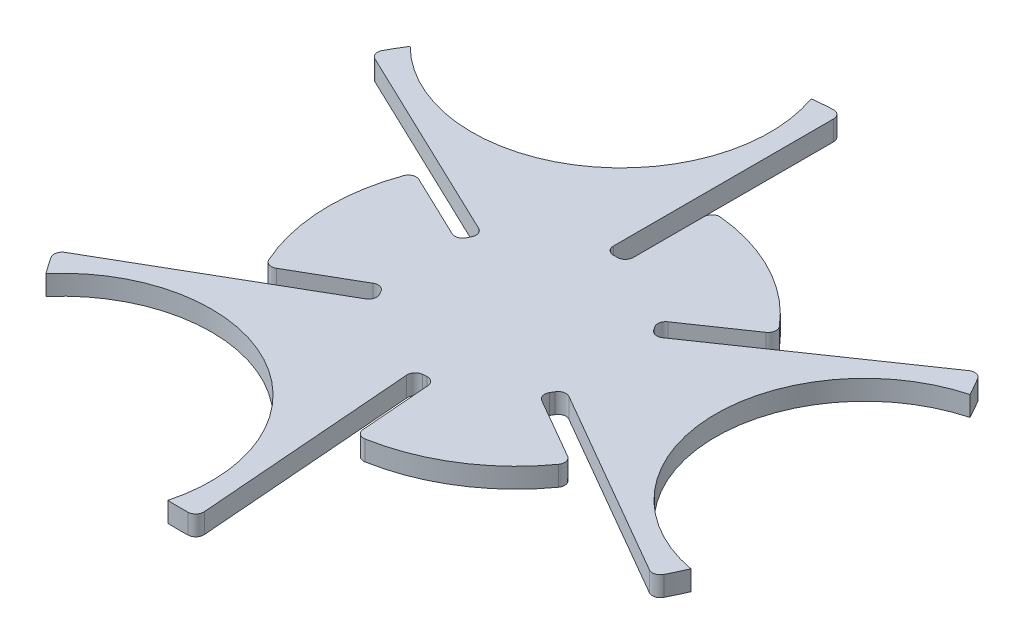
SolidWorks part; units mm, degrees
ref_plane "前基準面" through (0, 0, 0) normal (0, 0, 1) x (1, 0, 0)
ref_plane "上基準面" through (0, 0, 0) normal (0, 1, 0) x (1, 0, 0)
ref_plane "右基準面" through (0, 0, 0) normal (1, 0, 0) x (0, 0, -1)
sketch "草圖1" plane through (0, 0, 0) normal (0, 1, 0) x (1, 0, 0)
  line L2 (41.8956, -21.3017) -> (22.9006, -10.3349)
  line L8 (-2.5, 46.9335) -> (-2.5, 25)
  line L9 (-2.5, 25) -> (2.5, 25)
  line L10 (2.5, 46.9335) -> (2.5, 25)
  line L11 (22.9006, -10.3349) -> (20.4006, -14.6651)
  line L12 (39.3956, -25.6318) -> (20.4006, -14.6651)
  line L13 (-39.3956, -25.6318) -> (-20.4006, -14.6651)
  line L14 (-20.4006, -14.6651) -> (-22.9006, -10.3349)
  line L15 (-41.8956, -21.3017) -> (-22.9006, -10.3349)
  line L16 (20.6126, 14.1465) -> (0, 0) construction
  line L17 (4.4373, -24.7297) -> (6.1437, -46.5967)
  line L18 (22.0272, 12.0852) -> (40.1114, 24.4964)
  line L19 (19.1979, 16.2077) -> (37.2821, 28.6189)
  line L20 (19.1979, 16.2077) -> (22.0272, 12.0852)
  line L21 (-0.5475, -25.1187) -> (1.1588, -46.9857)
  line L22 (4.4373, -24.7297) -> (-0.5475, -25.1187)
  line L23 (-23.6352, 8.522) -> (-43.4258, 17.9778)
  line L24 (-21.4797, 13.0335) -> (-41.2702, 22.4893)
  line L25 (-23.6352, 8.522) -> (-21.4797, 13.0335)
  arc A35 (-2.5, 46.9335) -> (-41.2702, 22.4893) centre (0, 0) ccw
  circle A36 centre (0, 0) radius 25 construction
  arc A37 (41.8956, -21.3017) -> (40.1114, 24.4964) centre (0, 0) ccw
  arc A38 (-39.3956, -25.6318) -> (1.1588, -46.9857) centre (0, 0) ccw
  arc A39 (37.2821, 28.6189) -> (2.5, 46.9335) centre (0, 0) ccw
  arc A40 (-43.4258, 17.9778) -> (-41.8956, -21.3017) centre (0, 0) ccw
  arc A41 (6.1437, -46.5967) -> (39.3956, -25.6318) centre (0, 0) ccw
  point P1 (0, 25)
  dimension "D1" = 94
  dimension "D2" = 5
  dimension "D3" = 50
  dimension "D4" = 55.538
  dimension "D5" = 3
extrude "填料-伸長1" add sketch "草圖1" against normal blind 5
sketch "草圖2" plane through (0, 0, 0) normal (0, 1, 0) x (1, 0, 0)
  line L0 (-39.3956, -25.6318) -> (-71.8971, -44.3966)
  line L1 (1.1588, -46.9857) -> (4.0785, -84.4015)
  line L2 (-39.3693, -74.7684) -> (0, 0) construction
  line L3 (-0.5475, -25.1187) -> (1.1588, -46.9857) construction
  line L4 (-39.3956, -25.6318) -> (-20.4006, -14.6651) construction
  line L5 (-2.5, 46.9335) -> (-2.5, 84.463)
  line L6 (-41.2702, 22.4893) -> (-75.1331, 38.6687)
  line L7 (41.8956, -21.3017) -> (74.3971, -40.0664)
  line L8 (40.1114, 24.4964) -> (71.0546, 45.7328)
  arc A0 (-67.8465, -50.3696) -> (-3.1384, -84.4417) centre (0, 0) ccw construction
  arc A1 (-3.1384, -84.4417) -> (-67.8465, -50.3696) centre (-39.3693, -74.7684) ccw
  arc A2 (-71.5595, 44.9388) -> (-9.6981, 83.9416) centre (-45.0667, 71.479) ccw
  arc A3 (-71.8971, -44.3966) -> (-67.8465, -50.3696) centre (0, 0) ccw
  arc A4 (-3.1384, -84.4417) -> (4.0785, -84.4015) centre (0, 0) ccw
  arc A5 (-39.3956, -25.6318) -> (1.1588, -46.9857) centre (0, 0) ccw construction
  arc A6 (-2.5, 84.463) -> (-9.6981, 83.9416) centre (0, 0) ccw
  arc A7 (-71.5595, 44.9388) -> (-75.1331, 38.6687) centre (0, 0) ccw
  arc A8 (74.6979, 39.5029) -> (77.5446, -33.572) centre (84.436, 3.2894) ccw
  arc A9 (74.3971, -40.0664) -> (77.5446, -33.572) centre (0, 0) ccw
  arc A10 (74.6979, 39.5029) -> (71.0546, 45.7328) centre (0, 0) ccw
  arc A11 (-39.3956, -25.6318) -> (1.1588, -46.9857) centre (0, 0) ccw
  arc A12 (-2.5, 46.9335) -> (-41.2702, 22.4893) centre (0, 0) ccw
  arc A13 (41.8956, -21.3017) -> (40.1114, 24.4964) centre (0, 0) ccw
  dimension "D2" = 3
  dimension "D1" = 37.5
extrude "填料-伸長2" add sketch "草圖2" against normal up to surface (5 mm away) contours A11 L0 A3 A1 | A11 A1 A4 L1 | A13 L7 A9 A8 | A13 A8 A10 L8 | A12 L5 A6 A2 | A12 A2 A7 L6 up to face at (0, -5, 0)
fillet "圓角1" radius 2 24 edges at (-2.5, -2.5, -25) (2.5, -2.5, -25) (22.9006, -2.5, 10.3349) (20.4006, -2.5, 14.6651) (-20.4006, -2.5, 14.6651) (-22.9006, -2.5, 10.3349) (22.0272, -2.5, -12.0852) (19.1979, -2.5, -16.2077) (37.2821, -2.5, -28.6189) (2.5, -2.5, -46.9335) (-21.4797, -2.5, -13.0335) (-23.6352, -2.5, -8.522) (-43.4258, -2.5, -17.9778) (-41.8956, -2.5, 21.3017) (4.4373, -2.5, 24.7297) (-0.5475, -2.5, 25.1187) (6.1437, -2.5, 46.5967) (39.3956, -2.5, 25.6318) (74.3971, -2.5, 40.0664) (71.0546, -2.5, -45.7328) (-2.5, -2.5, -84.463) (-75.1331, -2.5, -38.6687) (-71.8971, -2.5, 44.3966) (4.0785, -2.5, 84.4015)
